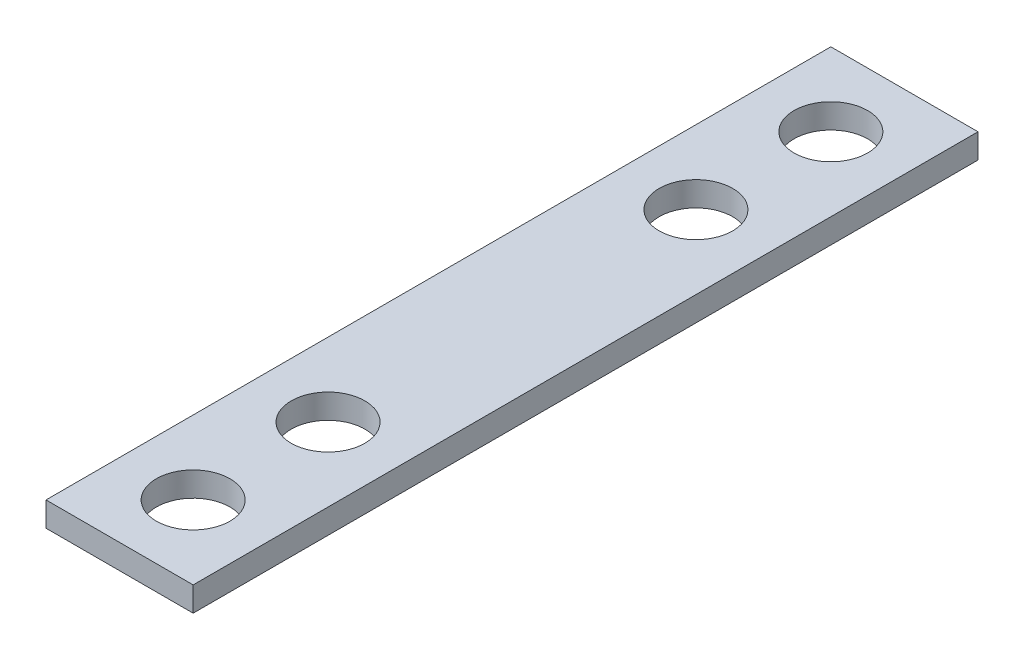
SolidWorks part; units mm, degrees
ref_plane "Спереди" through (0, 0, 0) normal (0, 0, 1) x (1, 0, 0)
ref_plane "Сверху" through (0, 0, 0) normal (0, 1, 0) x (1, 0, 0)
ref_plane "Справа" through (0, 0, 0) normal (1, 0, 0) x (0, 0, -1)
sketch "Эскиз1" plane through (0, 0, 0) normal (0, 1, 0) x (1, 0, 0)
  line L0 (0, 35) -> (0, 26) construction
  line L1 (-24, -10) -> (24, -10)
  line L2 (-20.4939, -16) -> (20.4939, -16)
  line L3 (-20.4939, 16) -> (20.4939, 16)
  line L4 (-24, 10) -> (24, 10)
  line L5 (0, 10) -> (0, -10)
  line L6 (-18, -13) -> (-18, 13)
  line L7 (0, 0) -> (-18, 0)
  line L8 (0, 10) -> (0, 16) construction
  line L9 (-18, 13) -> (0, 13) construction
  circle A0 centre (0, 0) radius 35
  circle A1 centre (0, 0) radius 26
  circle A2 centre (0, 30.5) radius 1.5
  circle A3 centre (21.5668, 21.5668) radius 1.5
  circle A4 centre (30.5, 0) radius 1.5
  circle A5 centre (21.5668, -21.5668) radius 1.5
  circle A6 centre (0, -30.5) radius 1.5
  circle A7 centre (-21.5668, -21.5668) radius 1.5
  circle A8 centre (-30.5, 0) radius 1.5
  circle A9 centre (-21.5668, 21.5668) radius 1.5
  circle A10 centre (-18, -13) radius 1.5
  circle A11 centre (-18, 13) radius 1.5
  circle A12 centre (-9, 13) radius 1.5
  circle A13 centre (-9, -13) radius 1.5
  circle A14 centre (0, 13) radius 1.5
  circle A15 centre (0, -13) radius 1.5
  circle A16 centre (9, 13) radius 1.5
  circle A17 centre (9, -13) radius 1.5
  circle A18 centre (18, 13) radius 1.5
  circle A19 centre (18, -13) radius 1.5
  point P24 (0, 0)
  dimension "D1" = 9
  dimension "D2" = 70
  dimension "D3" = 3
  dimension "D8" = 3
  dimension "D5" = 6
  dimension "D6" = 6
  dimension "D7" = 20
  dimension "D9" = 18
  dimension "D10" = 5
  dimension "D4" = 8
extrude "Бобышка-Вытянуть1" add sketch "Эскиз1" along normal blind 1
sketch "Эскиз2" plane through (0, 1, 0) normal (0, 1, 0) x (1, 0, 0)
  line L0 (-20.4939, 16) -> (20.4939, 16) construction
  line L1 (-12, 16) -> (-6, 16)
  line L2 (-12, 16) -> (-12, -16)
  line L3 (-12, -16) -> (-6, -16)
  line L5 (-20.4939, -16) -> (20.4939, -16) construction
  line L11 (-9, -7.5) -> (-9, -13) construction
  line L12 (-9, 7.5) -> (-9, 13) construction
  line L14 (-6, -16) -> (-6, 16)
  circle A0 centre (-9, -7.5) radius 1.5
  circle A1 centre (-9, 7.5) radius 1.5
  circle A2 centre (-9, -13) radius 1.5
  circle A3 centre (-9, 13) radius 1.5 construction
  circle A4 centre (-9, -13) radius 1.5 construction
  circle A5 centre (-9, 13) radius 1.5
  dimension "D1" = 3
  dimension "D2" = 6
  dimension "D3" = 15
extrude "Бобышка-Вытянуть2" add sketch "Эскиз2" along normal blind 1
sketch "Эскиз3" plane through (0, 0, 0) normal (0, -1, 0) x (1, 0, 0)
  circle A0 centre (0, 0) radius 35 construction
  circle A1 centre (0, 0) radius 35
extrude "Вырез-Вытянуть1" cut sketch "Эскиз3" against normal up to vertex (1 mm away)
